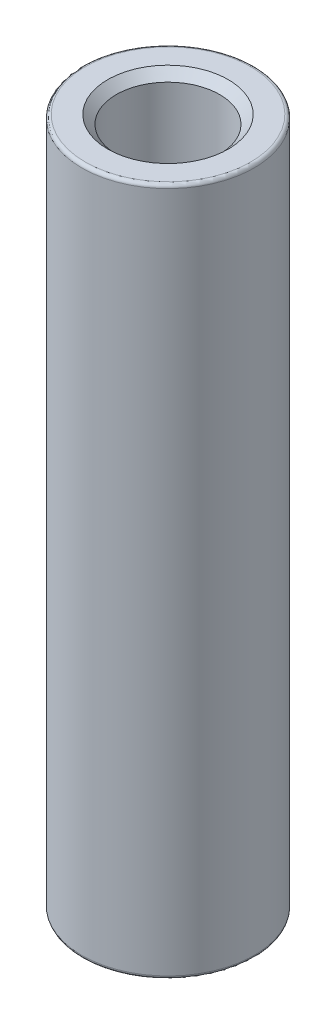
SolidWorks part; units mm, degrees
material "6063-T6"
ref_plane "Front Plane" through (0, 0, 0) normal (0, 0, 1) x (1, 0, 0)
ref_plane "Top Plane" through (0, 0, 0) normal (0, 1, 0) x (1, 0, 0)
ref_plane "Right Plane" through (0, 0, 0) normal (1, 0, 0) x (0, 0, -1)
sketch "Sketch1" plane through (0, 0, 0) normal (0, 1, 0) x (1, 0, 0)
  circle A0 centre (0, 0) radius 2.5
  circle A1 centre (0, 0) radius 1.5
  dimension "D1" = 3
  dimension "D2" = 5
extrude "Boss-Extrude1" add sketch "Sketch1" along normal mid plane 20
chamfer "Chamfer1" distance 0.25 angle 45 2 edges at (0, -10, 1.5) (0, 10, 1.5)
fillet "Fillet1" radius 0.1 2 edges at (0, -10, 2.5) (0, 10, 2.5)
